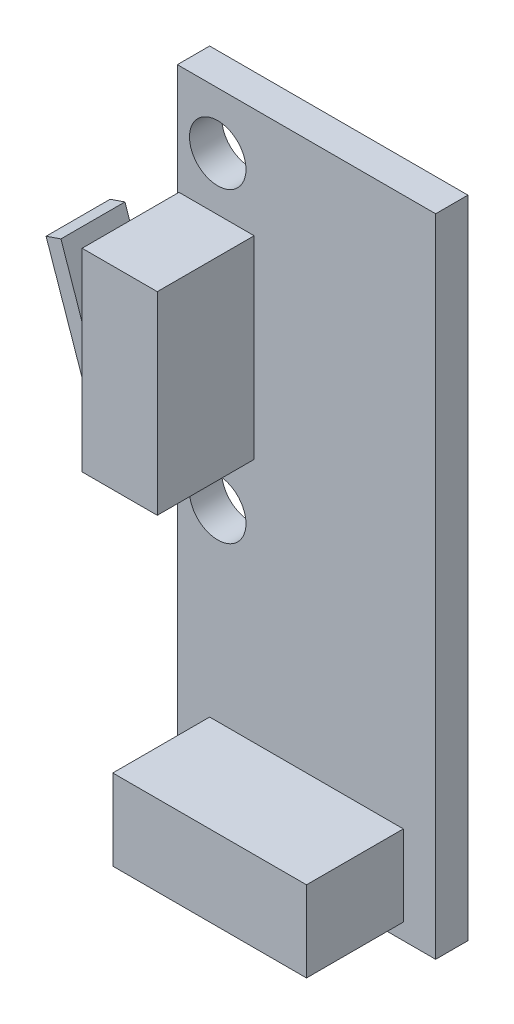
SolidWorks part; units mm, degrees
ref_plane "Plano frontal" through (0, 0, 0) normal (0, 0, 1) x (1, 0, 0)
ref_plane "Plano superior" through (0, 0, 0) normal (0, 1, 0) x (1, 0, 0)
ref_plane "Plano direito" through (0, 0, 0) normal (1, 0, 0) x (0, 0, -1)
sketch "Esboço1" plane through (0, 0, 0) normal (0, 0, 1) x (1, 0, 0)
  line L1 (-8, 20) -> (8, 20)
  line L2 (-8, 20) -> (-8, -20)
  line L3 (-8, -20) -> (8, -20)
  line L4 (8, 20) -> (8, -20)
  line L5 (-8, 20) -> (8, -20) construction
  line L6 (-8, -20) -> (8, 20) construction
  point P0 (0, 0)
  dimension "D1" = 40
  dimension "D2" = 16
extrude "Ressalto-extrusão1" add sketch "Esboço1" along normal blind 2
sketch "Esboço2" plane through (0, 0, 2) normal (0, 0, 1) x (1, 0, 0)
  line L0 (8, 20) -> (-8, 20) construction
  line L1 (-8, 20) -> (-8, -20) construction
  circle A0 centre (-5.5, 16.5) radius 1.75
  circle A1 centre (-5.5, -2.5) radius 1.75
  dimension "D1" = 3.5
  dimension "D2" = 19
  dimension "D3" = 3.5
  dimension "D4" = 2.5
extrude "Corte-extrusão1" cut sketch "Esboço2" against normal blind 2
sketch "Esboço3" plane through (0, 0, 2) normal (0, 0, 1) x (1, 0, 0)
  line L0 (8, 20) -> (-8, 20) construction
  line L1 (-7.9, 13.2) -> (-3.2438, 13.2)
  line L2 (-7.9, 13.2) -> (-7.9, 1.2)
  line L3 (-7.9, 1.2) -> (-3.2438, 1.2)
  line L4 (-3.2438, 13.2) -> (-3.2438, 1.2)
  line L5 (-7.9, 13.2) -> (-3.2438, 1.2) construction
  line L6 (-7.9, 1.2) -> (-3.2438, 13.2) construction
  line L8 (-8, 20) -> (-8, -20) construction
  point P4 (-5.5719, 7.2)
  dimension "D3" = 0.1
  dimension "D1" = 12.8
  dimension "D2" = 12
extrude "Ressalto-extrusão2" add sketch "Esboço3" along normal blind 6
sketch "Esboço4" plane through (0, 0, 2) normal (0, 0, 1) x (1, 0, 0)
  line L0 (-8, -20) -> (8, -20) construction
  line L1 (-6, -14) -> (6, -14)
  line L2 (-6, -14) -> (-6, -19)
  line L3 (-6, -19) -> (6, -19)
  line L4 (6, -14) -> (6, -19)
  line L5 (-6, -14) -> (6, -19) construction
  line L6 (-6, -19) -> (6, -14) construction
  point P4 (0, -16.5)
  dimension "D1" = 5
  dimension "D2" = 12
  dimension "D3" = 1
extrude "Ressalto-extrusão3" add sketch "Esboço4" along normal blind 6
sketch "Esboço5" plane through (-7.9, 0, 0) normal (-1, 0, 0) x (0, 0, 1)
  line L0 (8, 11.5613) -> (2, 11.5613)
  line L1 (8, 13.2) -> (8, 1.2) construction
  line L2 (2, 20) -> (2, -20) construction
ref_plane "Plano1" through (-4.3963, 12.7677, 0) normal (0.3256, -0.9455, 0) x (0, 0, -1)
sketch "Esboço6" plane through (-4.3963, 12.7677, 0) normal (0.3256, -0.9455, 0) x (0, 0, -1)
  line L0 (-8, -2.6764) -> (-2, -2.6764) construction
  line L1 (-6.9825, -5.757) -> (-3.0175, -5.757)
  line L2 (-6.9825, -5.757) -> (-6.9825, -6.7297)
  line L3 (-6.9825, -6.7297) -> (-3.0175, -6.7297)
  line L4 (-3.0175, -5.757) -> (-3.0175, -6.7297)
  line L5 (-6.9825, -5.757) -> (-3.0175, -6.7297) construction
  line L6 (-6.9825, -6.7297) -> (-3.0175, -5.757) construction
  point P4 (-5, -6.2434)
  point P7 (-5, -2.6764)
extrude "Ressalto-extrusão4" add sketch "Esboço6" along normal blind 9 and the other way blind 1.2
equation "\"d\"=3.44355"
